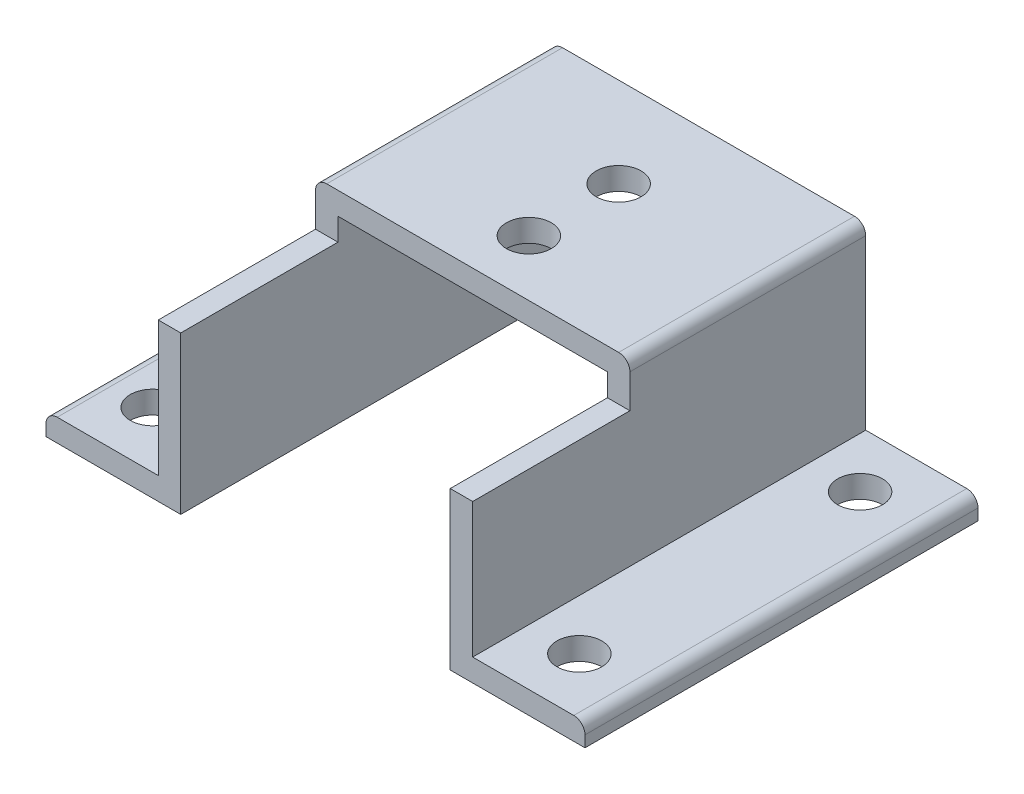
SolidWorks part; units mm, degrees
ref_plane "Front Plane" through (0, 0, 0) normal (0, 0, 1) x (1, 0, 0)
ref_plane "Top Plane" through (0, 0, 0) normal (0, 1, 0) x (1, 0, 0)
ref_plane "Right Plane" through (0, 0, 0) normal (1, 0, 0) x (0, 0, -1)
sketch "Sketch2" plane through (0, 0, 0) normal (0, 0, 1) x (1, 0, 0)
  line L0 (0, 0) -> (0, 2)
  line L1 (0, 2) -> (10, 2)
  line L2 (10, 2) -> (10, 18)
  line L3 (10, 18) -> (38, 18)
  line L4 (38, 18) -> (38, 2)
  line L5 (38, 2) -> (48, 2)
  line L6 (48, 2) -> (48, 0)
  line L7 (48, 0) -> (36, 0)
  line L8 (36, 0) -> (36, 16)
  line L9 (36, 16) -> (12, 16)
  line L10 (12, 16) -> (12, 0)
  line L11 (12, 0) -> (0, 0)
  dimension "D1" = 2
  dimension "D2" = 2
  dimension "D3" = 2
  dimension "D4" = 2
  dimension "D5" = 24
  dimension "D6" = 48
  dimension "D7" = 16
extrude "Boss-Extrude1" add sketch "Sketch2" along normal blind 35
sketch "Sketch3" plane through (0, 18, 0) normal (0, 1, 0) x (1, 0, 0)
  line L0 (38, -35) -> (38, 0) construction
  line L1 (10, -35) -> (38, -35)
  line L2 (10, -35) -> (10, -21)
  line L3 (10, -21) -> (38, -21)
  line L4 (38, -35) -> (38, -21)
  dimension "D1" = 14
extrude "Cut-Extrude1" cut sketch "Sketch3" against normal blind 4
fillet "Fillet1" radius 1 4 edges at (48, 2, 17.5) (0, 2, 17.5) (38, 18, 10.5) (10, 18, 10.5)
sketch "Sketch4" plane through (0, 18, 0) normal (0, 1, 0) x (1, 0, 0)
  line L0 (37, 0) -> (11, 0) construction
  line L1 (47, 0) -> (38, 0) construction
  circle A0 centre (24, -8) radius 2
  circle A1 centre (24, -16) radius 2
  circle A2 centre (42.5, -5) radius 2
  circle A3 centre (42.5, -30) radius 2
  circle A4 centre (4.5, -5) radius 2
  circle A5 centre (4.5, -30) radius 2
  dimension "D5" = 4
  dimension "D1" = 8
  dimension "D2" = 16
  dimension "D3" = 5
  dimension "D4" = 30
  dimension "D6" = 38
extrude "Cut-Extrude2" cut sketch "Sketch4" against normal through all
